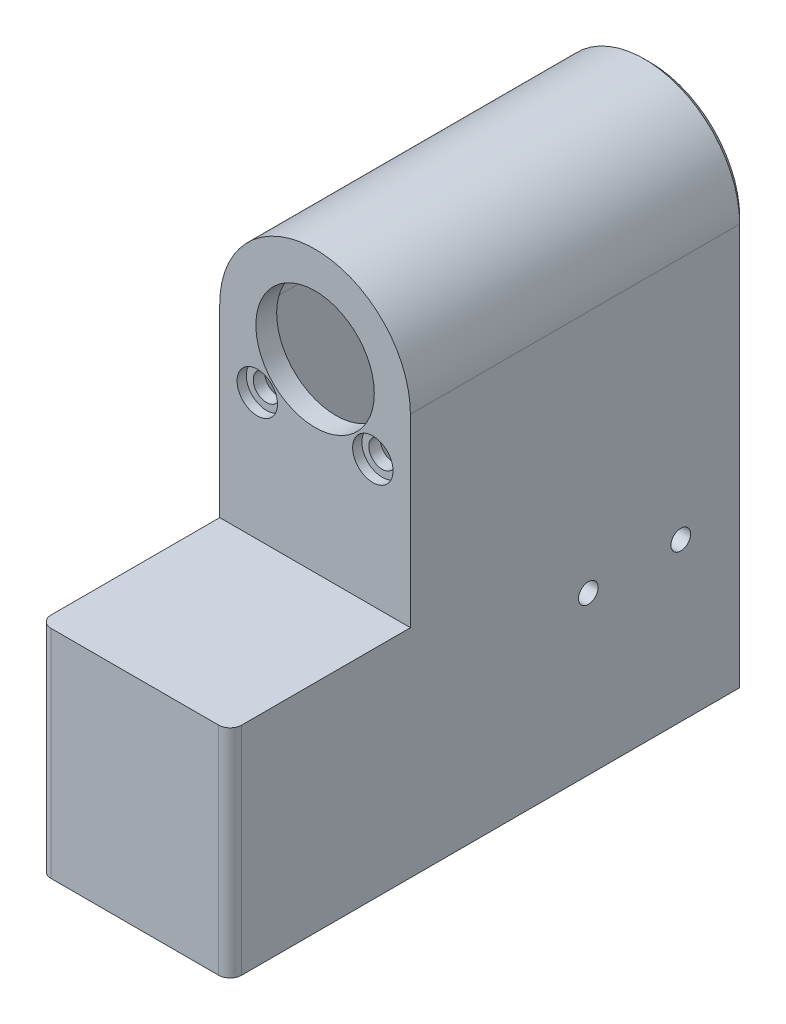
SolidWorks part; units mm, degrees
ref_plane "Front Plane" through (0, 0, 0) normal (0, 0, 1) x (1, 0, 0)
ref_plane "Top Plane" through (0, 0, 0) normal (0, 1, 0) x (1, 0, 0)
ref_plane "Right Plane" through (0, 0, 0) normal (1, 0, 0) x (0, 0, -1)
sketch "Sketch1" plane through (0, 0, 0) normal (0, 0, 1) x (1, 0, 0)
  line L0 (0, 0) -> (33, 0)
  line L1 (16.5, 0) -> (29, 0)
  line L2 (16.5, 0) -> (16.5, 9.4766)
  line L3 (4, 0) -> (4, 80.5)
  line L4 (29, 0) -> (29, 80.5)
  line L5 (0, 0) -> (0, 80.5)
  line L6 (0, 80.5) -> (4, 80.5)
  line L7 (33, 0) -> (33, 80.5)
  line L8 (33, 80.5) -> (29, 80.5)
  arc A0 (33, 80.5) -> (0, 80.5) centre (16.5, 80.5) ccw
  arc A1 (4, 80.5) -> (29, 80.5) centre (16.5, 80.5) cw
  point P5 (4, 0)
  dimension "D1" = 33
  dimension "D2" = 12.5
  dimension "D3" = 80.5
extrude "Boss-Extrude1" add sketch "Sketch1" along normal blind 71 contours L6 L5 L0 L3 | L6 A1 L8 A0 | L7 L8 L4 L0
sketch "Sketch2" plane through (0, 0, 71) normal (0, 0, 1) x (1, 0, 0)
  line L2 (33, 48.5) -> (0, 48.5)
  line L3 (0, 0) -> (0, 80.5) construction
  line L4 (0, 48.5) -> (0, 80.5)
  line L5 (33, 0) -> (33, 80.5) construction
  line L6 (33, 48.5) -> (33, 80.5)
  arc A0 (33, 80.5) -> (0, 80.5) centre (16.5, 80.5) ccw construction
  arc A1 (33, 80.5) -> (0, 80.5) centre (16.5, 80.5) ccw
  point P8 (16.5, 48.5)
extrude "Boss-Extrude2" add sketch "Sketch2" against normal blind 4
sketch "Sketch3" plane through (0, 0, 67) normal (0, 0, -1) x (-1, 0, 0)
  line L0 (-4, 48.5) -> (-29, 48.5) construction
  line L1 (-4, 48.5) -> (-29, 48.5)
  line L3 (-29, 44.5) -> (-4, 44.5)
  line L5 (0, 0) -> (0, 80.5) construction
  line L6 (0, 0) -> (0, 48.5)
  line L7 (-4, 48.5) -> (0, 48.5)
  line L8 (0, 0) -> (-3.8379, 0)
  line L9 (-4, 44.5) -> (-3.8379, 0)
  line L10 (-16.5, 44.5) -> (-16.5, 41.0104)
  line L11 (-33, 0) -> (-33, 48.5)
  line L12 (-29, 48.5) -> (-33, 48.5)
  line L13 (-29, 44.5) -> (-29.1621, 0)
  line L14 (-33, 0) -> (-29.1621, 0)
  line M8 (-29, 48.5) -> (-4, 48.5)
extrude "Boss-Extrude3" add sketch "Sketch3" against normal blind 34.2 contours L11 L14 L13 L3 L9 L8 L6 L7 L12 M8
sketch "Sketch4" plane through (0, 0, 0) normal (0, 0, -1) x (-1, 0, 0)
  line L6 (-4, 80.5) -> (-4, 0)
  line L7 (-4, 0) -> (0, 0)
  line L8 (0, 0) -> (0, 80.5)
  line L9 (-33, 80.5) -> (-33, 0)
  line L10 (-33, 0) -> (-29, 0)
  line L11 (-29, 0) -> (-29, 80.5)
  line L12 (-4, 80.5) -> (-4, 0)
  line L13 (-4, 0) -> (0, 0)
  line L14 (0, 0) -> (0, 80.5)
  line L15 (-33, 80.5) -> (-33, 0)
  line L16 (-33, 0) -> (-29, 0)
  line L17 (-29, 0) -> (-29, 80.5)
  arc A2 (0, 80.5) -> (-33, 80.5) centre (-16.5, 80.5) ccw
  arc A3 (-4, 80.5) -> (-29, 80.5) centre (-16.5, 80.5) ccw
  arc A4 (0, 80.5) -> (-33, 80.5) centre (-16.5, 80.5) ccw
  arc A5 (-4, 80.5) -> (-29, 80.5) centre (-16.5, 80.5) ccw
  dimension "D1" = 0
extrude "Cut-Extrude1" cut sketch "Sketch4" against normal blind 13
sketch "Sketch5" plane through (0, 0, 71) normal (0, 0, 1) x (1, 0, 0)
  line L0 (0, 80.5) -> (33, 80.5)
  circle A0 centre (16.5, 80.5) radius 10
  dimension "D1" = 20
extrude "Cut-Extrude2" cut sketch "Sketch5" against normal blind 13 contours L0 A0 | L0 A0
sketch "Sketch6" plane through (0, 0, 71) normal (0, 0, 1) x (1, 0, 0)
  line L0 (16.5, 70.5) -> (16.5, 73.1374)
  line L1 (16.5, 70.5) -> (33, 70.5)
  line L2 (33, 48.5) -> (33, 80.5) construction
  circle A0 centre (26.5, 70.5) radius 1.7
  circle A1 centre (6.5, 70.5) radius 1.7
  dimension "D2" = 3.4
  dimension "D1" = 6.5
extrude "Cut-Extrude3" cut sketch "Sketch6" against normal blind 13 contours A1 | L1 A0 | L1 A0
sketch "Sketch7" plane through (0, 0, 71) normal (0, 0, 1) x (1, 0, 0)
  circle A0 centre (6.5, 70.5) radius 3.25
  circle A1 centre (26.5, 70.5) radius 3.25
  dimension "D1" = 6.5
extrude "Cut-Extrude4" cut sketch "Sketch7" against normal blind 2.5
sketch "Sketch9" plane through (0, 0, 0) normal (0, -1, 0) x (1, 0, 0)
  line L0 (29.1621, 101.2) -> (29.1621, 71) construction
  line L1 (29.1621, 101.2) -> (29.1621, 71)
  line L2 (29.1621, 71) -> (29, 71)
  line L3 (29, 71) -> (29, 120)
  line L4 (29, 120) -> (29.1621, 101.2)
  line L6 (29, 67) -> (4, 67) construction
  line L7 (29, 67) -> (4, 67)
  line L8 (16.5, 67) -> (16.5, 71)
  line L9 (4, 120) -> (3.8379, 101.2)
  line L10 (4, 71) -> (4, 120)
  line L11 (3.8379, 71) -> (4, 71)
  line L12 (3.8379, 101.2) -> (3.8379, 71)
extrude "Boss-Extrude4" add sketch "Sketch9" against normal up to surface (44.5 mm away) contours L4 L1 L2 L3 | L9 L12 L11 L10 up to face at (16.5, 44.5, 79.7333)
sketch "Sketch10" plane through (0, 0, 101.2) normal (0, 0, 1) x (1, 0, 0)
  line L1 (40.2439, -6.5645) -> (-5.7585, -6.5645)
  line L2 (40.2439, -6.5645) -> (40.2439, 55.1467)
  line L3 (40.2439, 55.1467) -> (-5.7585, 55.1467)
  line L4 (-5.7585, -6.5645) -> (-5.7585, 55.1467)
  line L5 (40.2439, -6.5645) -> (-5.7585, 55.1467) construction
  line L6 (40.2439, 55.1467) -> (-5.7585, -6.5645) construction
  point P0 (17.2427, 24.2911)
extrude "Cut-Extrude5" cut sketch "Sketch10" along normal blind 42
sketch "Sketch11" plane through (0, 0, 101.2) normal (0, 0, 1) x (1, 0, 0)
  line L0 (29, 0) -> (4, 0)
  line L8 (4, 44.5) -> (29, 44.5)
  line L9 (29, 44.5) -> (29, 0)
  line L10 (29, 0) -> (33, 0)
  line L11 (33, 0) -> (33, 48.5)
  line L12 (33, 48.5) -> (0, 48.5)
  line L13 (0, 48.5) -> (0, 0)
  line L14 (0, 0) -> (4, 0)
  line L15 (4, 0) -> (4, 44.5)
  line L18 (29, 0) -> (33, 0)
  line L19 (33, 0) -> (33, 48.5)
  line L20 (33, 48.5) -> (0, 48.5)
  line L21 (0, 48.5) -> (0, 0)
  line L22 (0, 0) -> (4, 0)
  dimension "D1" = 0
extrude "Boss-Extrude5" add sketch "Sketch11" along normal blind 4
sketch "Sketch12" plane through (0, 0, 0) normal (0, -1, 0) x (1, 0, 0)
  line L8 (4, 13) -> (4, 101.2)
  line L9 (4, 101.2) -> (29, 101.2)
  line L10 (29, 101.2) -> (29, 13)
  line L11 (29, 13) -> (33, 13)
  line L12 (33, 13) -> (33, 105.2)
  line L13 (33, 105.2) -> (0, 105.2)
  line L14 (0, 105.2) -> (0, 13)
  line L15 (0, 13) -> (4, 13)
  line L16 (4, 13) -> (4, 101.2)
  line L17 (4, 101.2) -> (29, 101.2)
  line L18 (29, 101.2) -> (29, 13)
  line L19 (29, 13) -> (33, 13)
  line L20 (33, 13) -> (33, 105.2)
  line L21 (33, 105.2) -> (0, 105.2)
  line L22 (0, 105.2) -> (0, 13)
  line L23 (0, 13) -> (4, 13)
  dimension "D1" = 0
extrude "Cut-Extrude6" cut sketch "Sketch12" against normal blind 10.6
sketch "Sketch13" plane through (0, 0, 0) normal (-1, 0, 0) x (0, 0, 1)
  line L0 (105.2, 10.6) -> (13, 10.6) construction
  line L1 (13, 10.6) -> (13, 80.5) construction
  circle A0 centre (40.2, 38.3) radius 1.7
  circle A1 centre (24.2, 38.3) radius 1.7
  dimension "D1" = 27.7
  dimension "D2" = 3.4
  dimension "D3" = 27.2
  dimension "D4" = 16
extrude "Cut-Extrude7" cut sketch "Sketch13" against normal up to surface (33 mm away) contours A1 | A0 up to face at (33, 46.5333, 63.0667)
sketch "Sketch14" plane through (0, 0, 101.2) normal (0, 0, -1) x (-1, 0, 0)
  line L4 (-29, 10.6) -> (-4, 10.6)
  line L5 (-4, 10.6) -> (-4, 44.5)
  line L6 (-4, 44.5) -> (-29, 44.5)
  line L7 (-29, 44.5) -> (-29, 10.6)
  line L8 (-29, 10.6) -> (-4, 10.6)
  line L9 (-4, 10.6) -> (-4, 44.5)
  line L10 (-4, 44.5) -> (-29, 44.5)
  line L11 (-29, 44.5) -> (-29, 10.6)
  dimension "D1" = 0
extrude "Boss-Extrude6" add sketch "Sketch14" along normal blind 1
sketch "Sketch15" plane through (0, 10.6, 0) normal (0, -1, 0) x (1, 0, 0)
  line L0 (29, 100.2) -> (4, 100.2) construction
  line L1 (29, 100.2) -> (4, 100.2)
  line L2 (16.5, 100.2) -> (16.5, 101.5)
  line L3 (16.5, 105.2) -> (16.5, 103.9)
  line L4 (33, 105.2) -> (0, 105.2) construction
  line L5 (16.5, 101.5) -> (6.3, 101.5)
  line L6 (16.5, 101.5) -> (26.7, 101.5)
  line L7 (26.7, 101.5) -> (26.7, 103.9)
  line L8 (26.7, 103.9) -> (6.3, 103.9)
  line L9 (6.3, 103.9) -> (6.3, 101.5)
  dimension "D1" = 1.3
  dimension "D2" = 1.3
  dimension "D3" = 10.2
  dimension "D4" = 10.2
extrude "Cut-Extrude8" cut sketch "Sketch15" against normal blind 15 contours L8 L9 L5 L6 L7
sketch "Sketch16" plane through (0, 10.6, 0) normal (0, -1, 0) x (1, 0, 0)
  line L1 (26.7, 103.9) -> (6.3, 103.9) construction
  line L3 (21.7, 103.9) -> (21.7, 105.2)
  line L4 (33, 105.2) -> (0, 105.2) construction
  line L5 (21.7, 105.2) -> (11.3, 105.2)
  line L6 (11.3, 105.2) -> (11.3, 103.9)
  line L7 (21.7, 103.9) -> (11.3, 103.9)
  point P0 (16.5, 103.9)
  point P2 (16.5, 105.2)
  dimension "D1" = 10.4
extrude "Cut-Extrude9" cut sketch "Sketch16" against normal up to surface (15 mm away) up to face at (16.5, 25.6, 102.7)
sketch "Sketch17" plane through (0, 25.6, 0) normal (0, -1, 0) x (1, 0, 0)
  line L8 (26.7, 103.9) -> (21.7, 103.9)
  line L9 (21.7, 103.9) -> (21.7, 105.2)
  line L10 (21.7, 105.2) -> (11.3, 105.2)
  line L11 (11.3, 105.2) -> (11.3, 103.9)
  line L12 (11.3, 103.9) -> (6.3, 103.9)
  line L13 (6.3, 103.9) -> (6.3, 101.5)
  line L14 (6.3, 101.5) -> (26.7, 101.5)
  line L15 (26.7, 101.5) -> (26.7, 103.9)
  line L16 (26.7, 103.9) -> (21.7, 103.9)
  line L17 (21.7, 103.9) -> (21.7, 105.2)
  line L18 (21.7, 105.2) -> (11.3, 105.2)
  line L19 (11.3, 105.2) -> (11.3, 103.9)
  line L20 (11.3, 103.9) -> (6.3, 103.9)
  line L21 (6.3, 103.9) -> (6.3, 101.5)
  line L22 (6.3, 101.5) -> (26.7, 101.5)
  line L23 (26.7, 101.5) -> (26.7, 103.9)
  dimension "D1" = 0
extrude "popunio rupu" add sketch "Sketch17" along normal up to surface (15 mm away) up to face at (16.5, 10.6, 80.7375)
sketch "Sketch18" plane through (0, 0, 105.2) normal (0, 0, 1) x (1, 0, 0)
  line L4 (0, 48.5) -> (0, 10.6)
  line L5 (0, 10.6) -> (33, 10.6)
  line L6 (33, 10.6) -> (33, 48.5)
  line L7 (33, 48.5) -> (0, 48.5)
  line L8 (0, 48.5) -> (0, 10.6)
  line L9 (0, 10.6) -> (33, 10.6)
  line L10 (33, 10.6) -> (33, 48.5)
  line L11 (33, 48.5) -> (0, 48.5)
  dimension "D1" = 0
extrude "sasekao za tri mm" cut sketch "Sketch18" against normal blind 3
sketch "Sketch19" plane through (0, 0, 71) normal (0, 0, 1) x (1, 0, 0)
  circle A0 centre (6.5, 70.5) radius 3.25 construction
  circle A1 centre (6.5, 70.5) radius 3.25
  circle A2 centre (6.5, 70.5) radius 3.5
  circle A4 centre (26.5, 70.5) radius 3.5
  dimension "D1" = 7
extrude "pove'ao rupe za zavrtnje" cut sketch "Sketch19" against normal up to surface (2.5 mm away) up to face at (8.2, 70.5, 68.5)
sketch "Sketch20" plane through (0, 10.6, 0) normal (0, -1, 0) x (1, 0, 0)
  line L8 (33, 13) -> (33, 102.2)
  line L9 (33, 102.2) -> (0, 102.2)
  line L10 (0, 102.2) -> (0, 13)
  line L11 (0, 13) -> (4, 13)
  line L12 (4, 13) -> (4, 100.2)
  line L13 (4, 100.2) -> (29, 100.2)
  line L14 (29, 100.2) -> (29, 13)
  line L15 (29, 13) -> (33, 13)
  line L16 (33, 13) -> (33, 102.2)
  line L17 (33, 102.2) -> (0, 102.2)
  line L18 (0, 102.2) -> (0, 13)
  line L19 (0, 13) -> (4, 13)
  line L20 (4, 13) -> (4, 100.2)
  line L21 (4, 100.2) -> (29, 100.2)
  line L22 (29, 100.2) -> (29, 13)
  line L23 (29, 13) -> (33, 13)
  dimension "D1" = 0
extrude "skratio dno" cut sketch "Sketch20" against normal blind 0.4
sketch "Sketch21" plane through (0, 44.5, 0) normal (0, -1, 0) x (1, 0, 0)
  line L4 (29, 100.2) -> (4, 100.2)
  line L5 (4, 100.2) -> (4, 67)
  line L6 (4, 67) -> (29, 67)
  line L7 (29, 67) -> (29, 100.2)
  line L8 (29, 100.2) -> (4, 100.2)
  line L9 (4, 100.2) -> (4, 67)
  line L10 (4, 67) -> (29, 67)
  line L11 (29, 67) -> (29, 100.2)
  dimension "D1" = 0
extrude "napravio malo vi[e mesta za vrh razvodnika" cut sketch "Sketch21" against normal blind 0.4
sketch "Sketch22" plane through (0, 0, 67) normal (0, 0, -1) x (-1, 0, 0)
  line L3 (-29, 44.9) -> (-4, 44.9)
  line L4 (-4, 44.9) -> (-4, 80.5)
  line L5 (-29, 80.5) -> (-29, 44.9)
  line L6 (-29, 44.9) -> (-4, 44.9)
  line L7 (-4, 44.9) -> (-4, 80.5)
  line L8 (-29, 80.5) -> (-29, 44.9)
  arc A1 (-4, 80.5) -> (-29, 80.5) centre (-16.5, 80.5) ccw
  arc A2 (-4, 80.5) -> (-29, 80.5) centre (-16.5, 80.5) ccw
  dimension "D1" = 0
extrude "skratio ceoni deo" cut sketch "Sketch22" against normal blind 0.4
sketch "Sketch23" plane through (0, 0, 13) normal (0, 0, -1) x (-1, 0, 0)
  line L0 (-29, 80.5) -> (-29, 11)
  line L1 (-29, 11) -> (-29.2, 11)
  line L2 (-29.2, 11) -> (-29.2, 80.5)
  line L3 (-16.5, 80.5) -> (-16.5, 75.0754)
  line L4 (-4, 11) -> (-3.8, 11)
  line L5 (-3.8, 11) -> (-3.8, 80.5)
  line L6 (-4, 80.5) -> (-4, 11) construction
  line L7 (-4, 80.5) -> (-4, 11)
  arc A0 (-4, 80.5) -> (-29, 80.5) centre (-16.5, 80.5) ccw construction
  arc A1 (-4, 80.5) -> (-29, 80.5) centre (-16.5, 80.5) ccw
  arc A2 (-29.2, 80.5) -> (-3.8, 80.5) centre (-16.5, 80.5) cw
extrude "napravio mesta za drzac 1" cut sketch "Sketch23" against normal up to surface (54.4 mm away) contours L0 L1 L2 A2 L5 L4 L7 A1 up to face at (4.8, 70.5, 67.4)
sketch "Sketch24" plane through (0, 0, 67.4) normal (0, 0, -1) x (-1, 0, 0)
  line L0 (-3.8, 80.5) -> (-3.8, 11) construction
  line L1 (-3.8, 11) -> (-4, 11) construction
  line L2 (-4, 11) -> (-4, 44.9) construction
  line L3 (-29.2, 11) -> (-29, 11) construction
  line L4 (-29.2, 80.5) -> (-29.2, 11) construction
  line L5 (-29, 11) -> (-29, 44.9) construction
  line L6 (-3.8, 44.9) -> (-3.8, 11)
  line L7 (-3.8, 11) -> (-4, 11)
  line L8 (-4, 11) -> (-4, 44.9)
  line L9 (-29.2, 11) -> (-29, 11)
  line L10 (-29.2, 44.9) -> (-29.2, 11)
  line L11 (-29, 11) -> (-29, 44.9)
  line L12 (-29.2, 44.9) -> (-29, 44.9)
  line L13 (-4, 44.9) -> (-3.8, 44.9)
extrude "napravio emsta za drzac 2" cut sketch "Sketch24" against normal up to surface (32.8 mm away)
chamfer "Chamfer1" distance 1 angle 45 2 edges at (1.9, 11, 13) (31.1, 11, 13)
sketch "Sketch26" plane through (0, 0, 68.5) normal (0, 0, 1) x (1, 0, 0)
  circle A0 centre (26.5, 70.5) radius 2.3
  circle A1 centre (6.5, 70.5) radius 2.3
  dimension "D1" = 4.6
  dimension "D2" = 4.6
extrude "povecao otvor za M3" cut sketch "Sketch26" against normal up to surface (1.1 mm away) up to face at (16.5, 65.875, 67.4)
sketch "Sketch27" plane through (0, 0, 71) normal (0, 0, 1) x (1, 0, 0)
  circle A0 centre (16.5, 80.5) radius 10.25
  dimension "D1" = 20.5
extrude "povecao otvor za prikljucak" cut sketch "Sketch27" against normal blind 10
sketch "Sketch28" plane through (0, 0, 100.2) normal (0, 0, -1) x (-1, 0, 0)
  line L4 (-3.8, 44.9) -> (-29.2, 44.9)
  line L5 (-29.2, 44.9) -> (-29.2, 11)
  line L6 (-29.2, 11) -> (-3.8, 11)
  line L7 (-3.8, 11) -> (-3.8, 44.9)
  line L8 (-3.8, 44.9) -> (-29.2, 44.9)
  line L9 (-29.2, 44.9) -> (-29.2, 11)
  line L10 (-29.2, 11) -> (-3.8, 11)
  line L11 (-3.8, 11) -> (-3.8, 44.9)
  dimension "D1" = 0
extrude "Boss-Extrude7" add sketch "Sketch28" along normal blind 2
fillet "zaobljenje za prst" radius 2 4 edges at (29.2, 27.95, 98.2) (3.8, 27.95, 98.2) (33, 29.75, 102.2) (0, 29.75, 102.2)
chamfer "oborena ivica za šaku" distance 1 angle 45 3 edges at (0, 46.25, 13) (16.5, 97, 13) (33, 46.25, 13)
sketch "Sketch29" plane through (0, 0, 68.5) normal (0, 0, 1) x (1, 0, 0)
  circle A0 centre (6.5, 70.5) radius 3.5 construction
  circle A1 centre (6.5, 70.5) radius 3.5
  circle A2 centre (6.5, 70.5) radius 2.3 construction
  circle A3 centre (6.5, 70.5) radius 2.3
  circle A4 centre (26.5, 70.5) radius 2.3 construction
  circle A5 centre (26.5, 70.5) radius 2.3
  circle A6 centre (26.5, 70.5) radius 3.5 construction
  circle A7 centre (26.5, 70.5) radius 3.5
extrude "Boss-Extrude8" add sketch "Sketch29" along normal blind 0.9
sketch "Sketch30" plane through (0, 0, 0) normal (-1, 0, 0) x (0, 0, 1)
  circle A0 centre (24.2, 38.3) radius 3.5
  circle A1 centre (40.2, 38.3) radius 3.5
  dimension "D1" = 7
extrude "Cut-Extrude10" cut sketch "Sketch30" against normal blind 2
